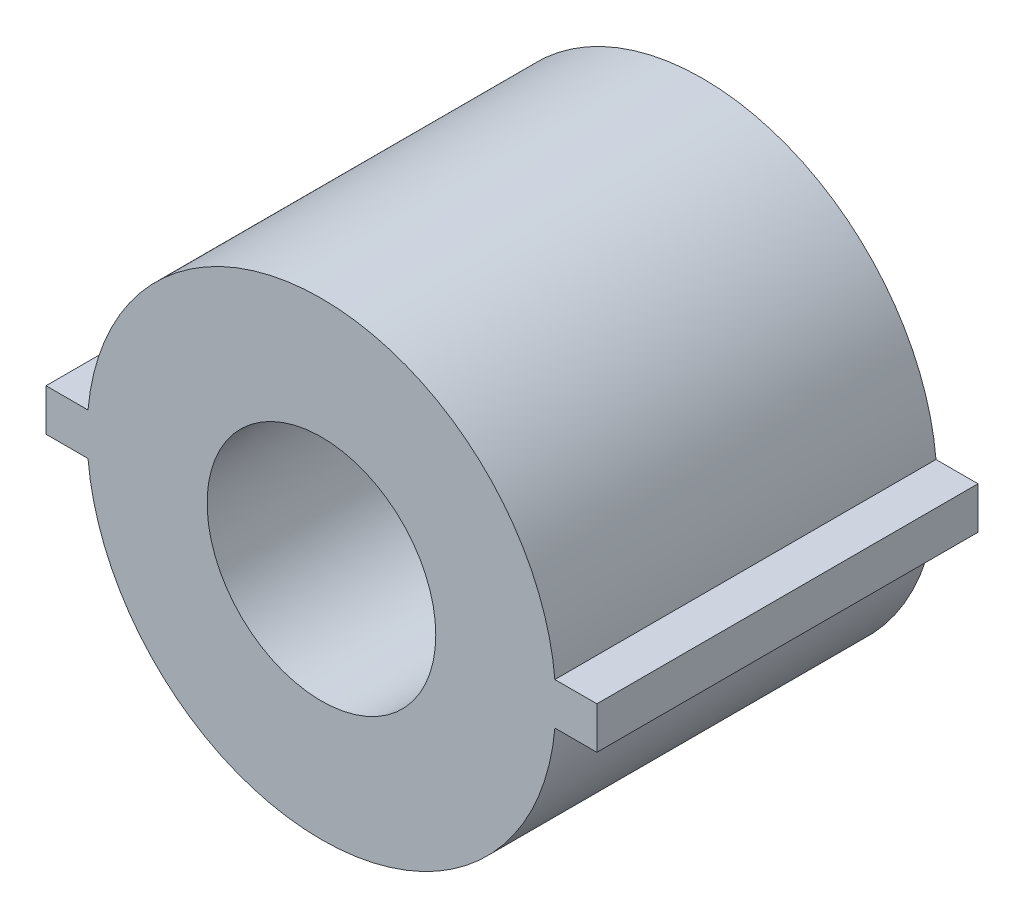
SolidWorks part; units mm, degrees
ref_plane "Front Plane" through (0, 0, 0) normal (0, 0, 1) x (1, 0, 0)
ref_plane "Top Plane" through (0, 0, 0) normal (0, 1, 0) x (1, 0, 0)
ref_plane "Right Plane" through (0, 0, 0) normal (1, 0, 0) x (0, 0, -1)
sketch "Sketch1" plane through (0, 0, 0) normal (0, 0, 1) x (1, 0, 0)
  circle A0 centre (0, 0) radius 1.905
  circle A1 centre (0, 0) radius 3.905
  dimension "D1" = 3.81
  dimension "D3" = 7.81
  dimension "D2" = 2
extrude "Boss-Extrude1" add sketch "Sketch1" along normal blind 6.35
sketch "Sketch2" plane through (0, 0, 0) normal (0, 0, -1) x (-1, 0, 0)
  line L0 (0, 0) -> (0, -4.2696) construction
  line L1 (0, 0) -> (9.1786, 0) construction
  line L2 (4.5893, 0.35) -> (4.5893, -0.35)
  line L3 (4.5893, -0.35) -> (3.8893, -0.35)
  line L4 (3.8893, -0.35) -> (3.8893, 0.35)
  line L5 (4.5893, 0.35) -> (3.8893, 0.35)
  line L6 (-4.5893, -0.35) -> (-3.8893, -0.35)
  line L7 (-4.5893, 0.35) -> (-4.5893, -0.35)
  line L8 (-4.5893, 0.35) -> (-3.8893, 0.35)
  line L9 (-3.8893, -0.35) -> (-3.8893, 0.35)
  circle A1 centre (0, 0) radius 3.905 construction
  point P8 (0, 0)
  point P11 (3.8893, 0)
  point P12 (4.5893, 0)
  point P16 (0, 0)
  point P17 (0, 0)
  dimension "D1" = 0.7
  dimension "D2" = 0.7
extrude "Boss-Extrude2" add sketch "Sketch2" against normal blind 6.35
